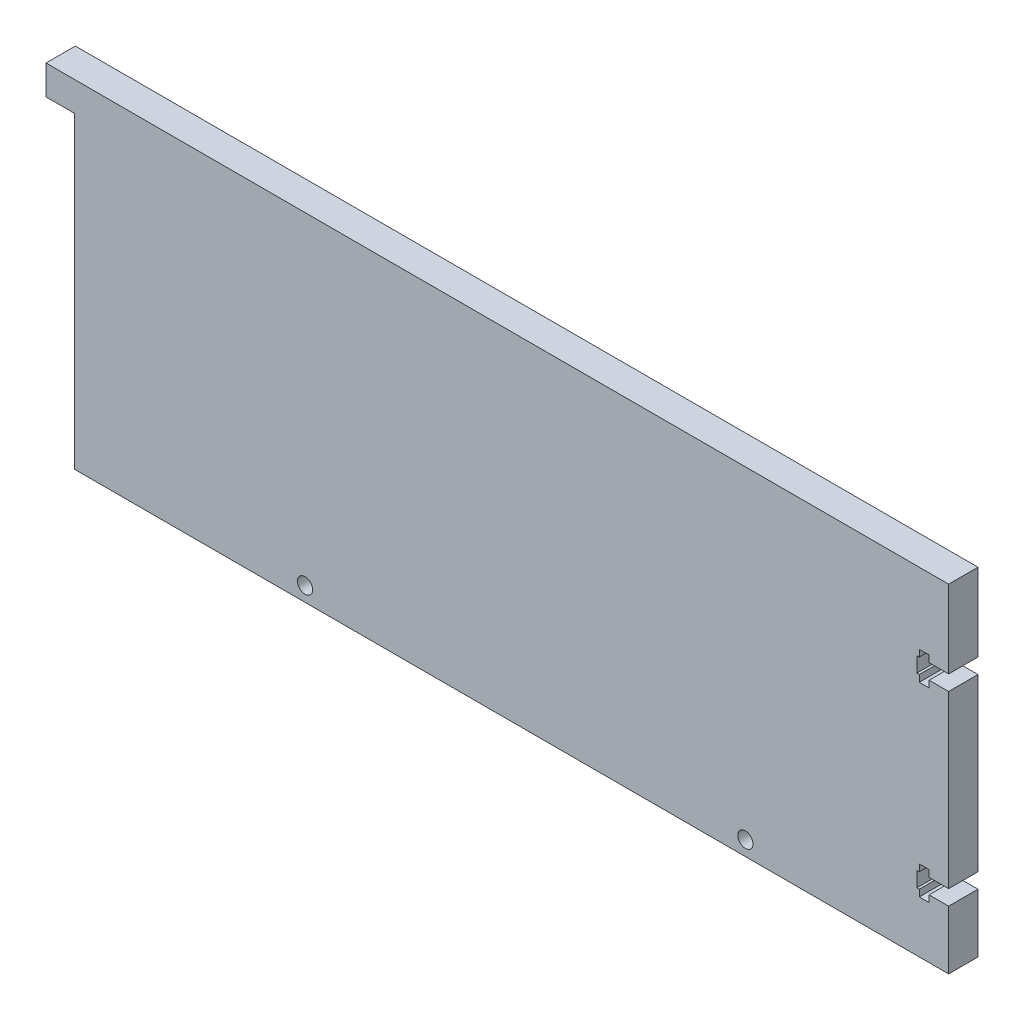
SolidWorks part; units mm, degrees
ref_plane "Płaszczyzna przednia" through (0, 0, 0) normal (0, 0, 1) x (1, 0, 0)
ref_plane "Płaszczyzna górna" through (0, 0, 0) normal (0, 1, 0) x (1, 0, 0)
ref_plane "Płaszczyzna prawa" through (0, 0, 0) normal (1, 0, 0) x (0, 0, -1)
sketch "Szkic1" plane through (0, 0, 0) normal (0, 0, 1) x (1, 0, 0)
  line L0 (172.7, 107.5949) -> (172.7, 38.5949)
  line L1 (172.7, 107.5949) -> (-6, 107.5949)
  line L2 (172.7, 38.5949) -> (-6, 38.5949)
  line L3 (-6, 107.5949) -> (-6, 38.5949)
  dimension "D2" = 69
  dimension "D3" = 178.7
extrude "Dodanie-wyciągnięcie1" add sketch "Szkic1" against normal blind 6
sketch "Szkic2" plane through (0, 0, -6) normal (0, 0, -1) x (-1, 0, 0)
  line L0 (-129.6, 44.5949) -> (-129.6, 38.5949) construction
  line L1 (-129.6, 44.5949) -> (-129.6, 38.5949)
  line L2 (-132.7, 44.5949) -> (-132.7, 38.5949) construction
  line L3 (-42.7, 44.5949) -> (-42.7, 38.5949) construction
  line L4 (6, 107.5949) -> (-172.7, 107.5949)
  line L5 (-172.7, 107.5949) -> (-172.7, 38.5949)
  line L6 (-172.7, 38.5949) -> (6, 38.5949)
  line L7 (6, 38.5949) -> (6, 107.5949)
  line L8 (6, 107.5949) -> (-172.7, 107.5949)
  line L9 (-172.7, 107.5949) -> (-172.7, 38.5949)
  line L10 (-172.7, 38.5949) -> (6, 38.5949)
  line L11 (6, 38.5949) -> (6, 107.5949)
  line L12 (-39.6, 44.5949) -> (-39.6, 38.5949) construction
  line L13 (-132.7, 44.5949) -> (-132.7, 38.5949)
  line L14 (-42.7, 44.5949) -> (-42.7, 38.5949)
  line L15 (-39.6, 44.5949) -> (-39.6, 38.5949)
  line L16 (-132.7, 41.5949) -> (-129.6, 41.5949)
  line L17 (-42.7, 41.5949) -> (-39.6, 41.5949)
  circle A0 centre (-41.15, 41.5949) radius 1.55
  circle A1 centre (-131.15, 41.5949) radius 1.55
  dimension "D2" = 3.1
  dimension "D3" = 3.1
  dimension "D1" = 0
sketch "Szkic3" plane through (0, 0, -6) normal (0, 0, -1) x (-1, 0, 0)
  circle A0 centre (-41.15, 41.5949) radius 1.55 construction
  circle A1 centre (-41.15, 41.5949) radius 1.55
  circle A2 centre (-131.15, 41.5949) radius 1.55 construction
  circle A3 centre (-131.15, 41.5949) radius 1.55
extrude "Wytnij-wyciągnięcie1" cut sketch "Szkic3" against normal through all
sketch "Szkic4" plane through (0, 0, -6) normal (0, 0, -1) x (-1, 0, 0)
  line L0 (-172.7, 50.5949) -> (-172.7, 53.6949)
  line L1 (-172.7, 50.5949) -> (-168.7, 50.5949)
  line L2 (-172.7, 53.6949) -> (-168.7, 53.6949)
  line L3 (-166.2, 50.5949) -> (-166.2, 53.6949)
  line L4 (-172.7, 38.5949) -> (-172.7, 107.5949) construction
  line L5 (-168.7, 49.2199) -> (-166.7, 49.2199)
  line L6 (-168.7, 49.2199) -> (-168.7, 50.5949)
  line L7 (-166.7, 49.2199) -> (-166.7, 50.5949)
  line L8 (-168.7, 55.0699) -> (-166.7, 55.0699)
  line L9 (-168.7, 53.6949) -> (-168.7, 55.0699)
  line L10 (-166.7, 50.5949) -> (-166.2, 50.5949)
  line L11 (-166.7, 53.6949) -> (-166.7, 55.0699)
  line L12 (-166.7, 53.6949) -> (-166.2, 53.6949)
  line L13 (6, 38.5949) -> (-172.7, 38.5949) construction
  dimension "D1" = 5.85
  dimension "D2" = 1.375
  dimension "D3" = 3.1
  dimension "D4" = 6.5
  dimension "D5" = 2
  dimension "D6" = 0.5
  dimension "D7" = 12
extrude "Wytnij-wyciągnięcie2" cut sketch "Szkic4" against normal through all
pattern_linear "Szyk liniowy1" count 2 spacing 38 along (0, 1, 0) of "Wytnij-wyciągnięcie2"
sketch "Szkic5" plane through (-6, 0, 0) normal (-1, 0, 0) x (0, 0, 1)
  line L0 (-6, 107.5949) -> (-6, 101.5949)
  line L1 (-6, 107.5949) -> (0, 107.5949)
  line L2 (-6, 101.5949) -> (0, 101.5949)
  line L3 (0, 107.5949) -> (0, 101.5949)
  line L4 (-6, 107.5949) -> (-6, 38.5949) construction
  dimension "D1" = 6
  dimension "D2" = 6
extrude "Dodanie-wyciągnięcie2" add sketch "Szkic5" along normal blind 5.8
equation "\"tolerancja_wpusy\"=0.2"
equation "\"dlugosc_wpustu_duzy\"=20"
equation "\"srednica_otworu_M3\"=3.1"
equation "\"szerokosc_nogi_T\"=3.1"
equation "\"dlugosc_T_30\"=11"
equation "\"grubosc_na_nakretke_kwadrat\"=2"
equation "\"szerokosc_na_nakretke_kwadrat\"=5.85"
equation "\"wyokosc_nadstawki_T\"=0.5"
equation "\"dlugosc_T_20_6\"=14"
equation "\"D2@Szkic2\"=\"srednica_otworu_M3\""
equation "\"D3@Szkic2\"=\"srednica_otworu_M3\""
equation "\"D1@Szkic4\"=\"szerokosc_na_nakretke_kwadrat\""
equation "\"D2@Szkic4\"=(\"szerokosc_na_nakretke_kwadrat\"-\"szerokosc_nogi_T\")/2"
equation "\"D3@Szkic4\"=\"szerokosc_nogi_T\""
equation "\"D5@Szkic4\"=\"grubosc_na_nakretke_kwadrat\""
equation "\"D6@Szkic4\"=\"wyokosc_nadstawki_T\""
